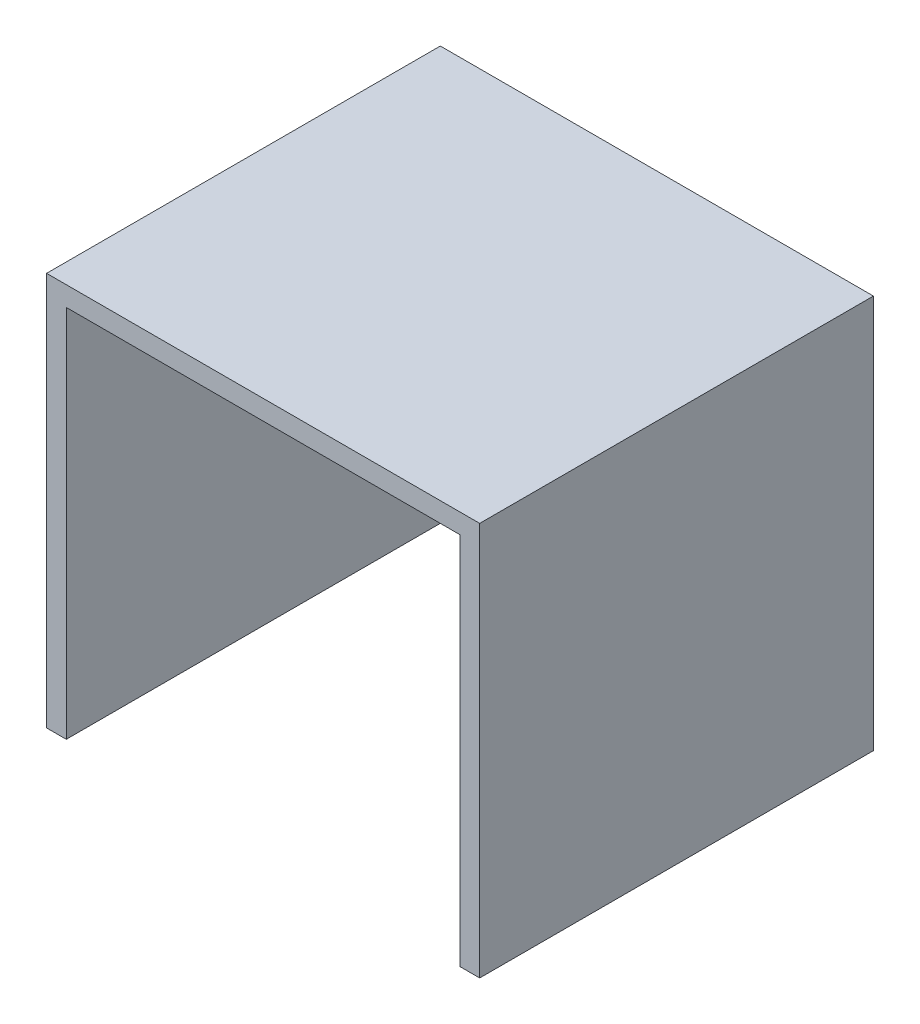
SolidWorks part; units mm, degrees
ref_plane "Front Plane" through (0, 0, 0) normal (0, 0, 1) x (1, 0, 0)
ref_plane "Top Plane" through (0, 0, 0) normal (0, 1, 0) x (1, 0, 0)
ref_plane "Right Plane" through (0, 0, 0) normal (1, 0, 0) x (0, 0, -1)
sketch "Sketch1" plane through (0, 0, 0) normal (0, 0, 1) x (1, 0, 0)
  line L0 (2, -2) -> (2, -40)
  line L1 (0, 0) -> (44, 0)
  line L2 (0, 0) -> (0, -40)
  line L3 (2, -2) -> (42, -2)
  line L4 (44, 0) -> (44, -40)
  line L5 (42, -2) -> (42, -40)
  line L6 (0, -40) -> (2, -40)
  line L7 (42, -40) -> (44, -40)
  dimension "D1" = 44
  dimension "D2" = 40
  dimension "D3" = 2
extrude "Boss-Extrude1" add sketch "Sketch1" along normal blind 40
